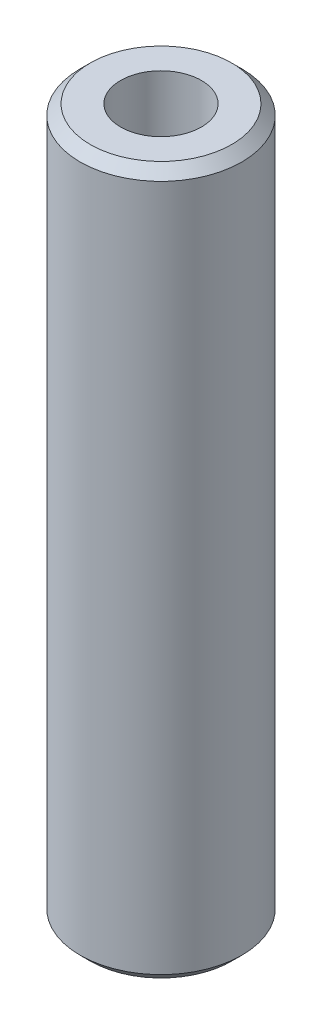
SolidWorks part; units mm, degrees
ref_plane "Front Plane" through (0, 0, 0) normal (0, 0, 1) x (1, 0, 0)
ref_plane "Top Plane" through (0, 0, 0) normal (0, 1, 0) x (1, 0, 0)
ref_plane "Right Plane" through (0, 0, 0) normal (1, 0, 0) x (0, 0, -1)
sketch "Sketch1" plane through (0, 0, 0) normal (0, 1, 0) x (1, 0, 0)
  circle A1 centre (0, 0) radius 2
  circle A2 centre (0, 0) radius 4
  dimension "D1" = 4
  dimension "D2" = 2
extrude "Boss-Extrude1" add sketch "Sketch1" along normal blind 35
chamfer "Chamfer1" distance 0.5 angle 45 2 edges at (0, 0, 4) (0, 35, 4)
